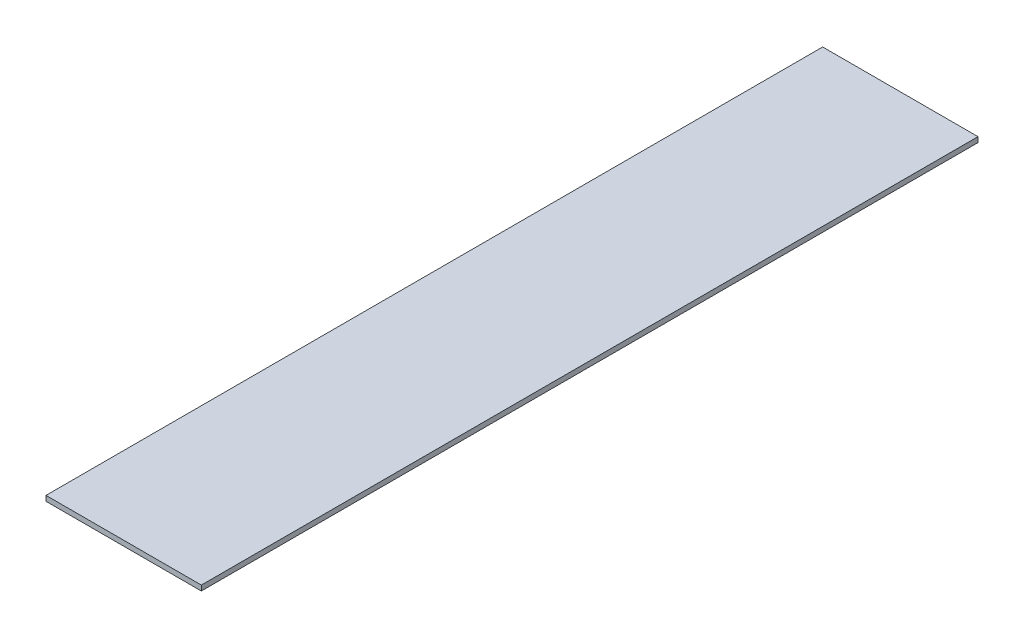
SolidWorks part; units mm, degrees
material "Thornel Mat VMA"
ref_plane "Front Plane" through (0, 0, 0) normal (0, 0, 1) x (1, 0, 0)
ref_plane "Top Plane" through (0, 0, 0) normal (0, 1, 0) x (1, 0, 0)
ref_plane "Right Plane" through (0, 0, 0) normal (1, 0, 0) x (0, 0, -1)
sketch "Sketch1" plane through (0, 0, 0) normal (0, 1, 0) x (1, 0, 0)
  line L1 (0, 0) -> (38.1, 0)
  line L2 (0, 0) -> (0, -190.5)
  line L3 (0, -190.5) -> (38.1, -190.5)
  line L4 (38.1, 0) -> (38.1, -190.5)
  dimension "D1" = 38.1
  dimension "D2" = 190.5
extrude "Boss-Extrude1" add sketch "Sketch1" along normal blind 1.27
